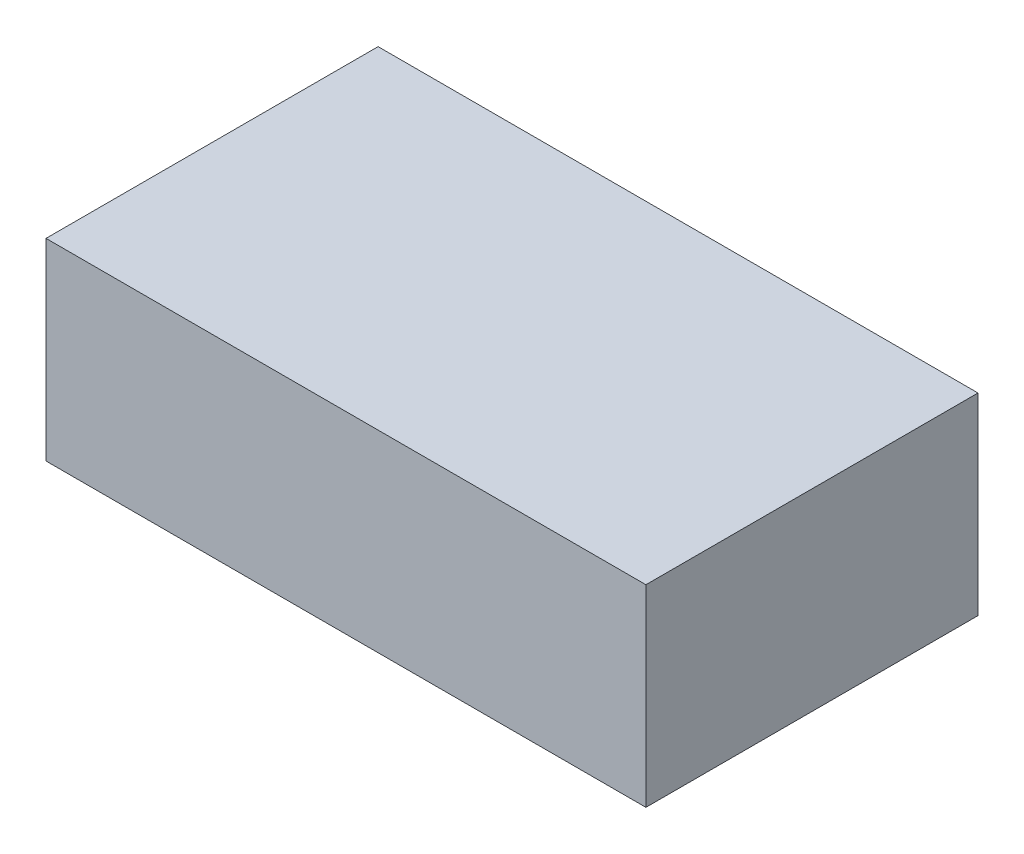
SolidWorks part; units mm, degrees
ref_plane "Front Plane" through (0, 0, 0) normal (0, 0, 1) x (1, 0, 0)
ref_plane "Top Plane" through (0, 0, 0) normal (0, 1, 0) x (1, 0, 0)
ref_plane "Right Plane" through (0, 0, 0) normal (1, 0, 0) x (0, 0, -1)
sketch "Sketch1" plane through (0, 0, 0) normal (0, 1, 0) x (1, 0, 0)
  line L1 (0, 0.5152) -> (56, 0.5152)
  line L2 (0, 0.5152) -> (0, 31.5152)
  line L3 (0, 31.5152) -> (56, 31.5152)
  line L4 (56, 0.5152) -> (56, 31.5152)
  dimension "D1" = 56
  dimension "D2" = 31
extrude "Boss-Extrude1" add sketch "Sketch1" along normal blind 18
